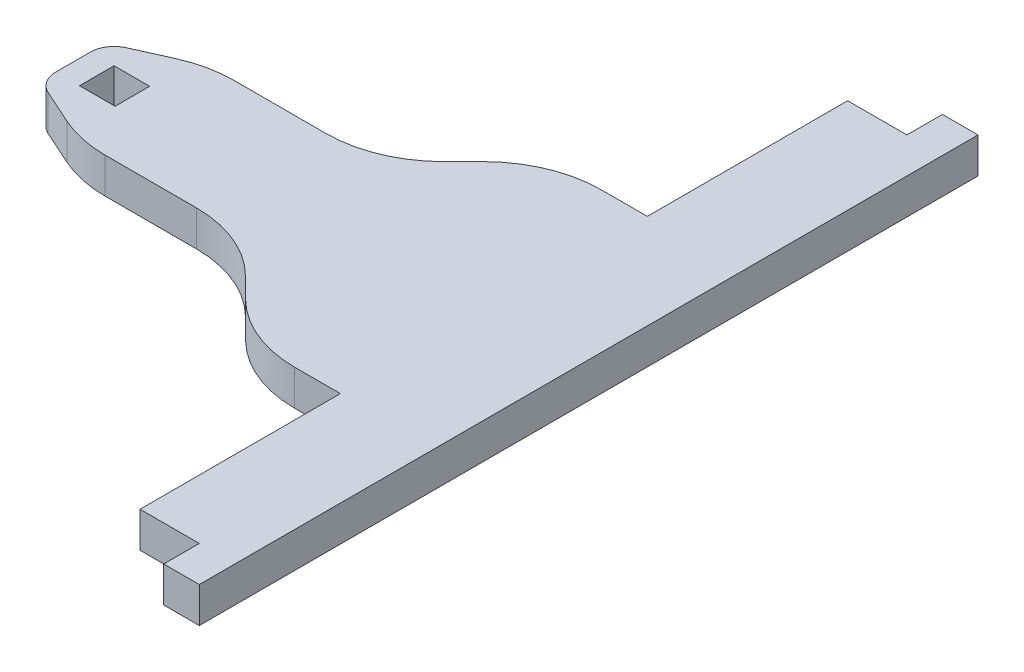
SolidWorks part; units mm, degrees
ref_plane "Front Plane" through (0, 0, 0) normal (0, 0, 1) x (1, 0, 0)
ref_plane "Top Plane" through (0, 0, 0) normal (0, 1, 0) x (1, 0, 0)
ref_plane "Right Plane" through (0, 0, 0) normal (1, 0, 0) x (0, 0, -1)
sketch "Sketch1" plane through (0, 0, 0) normal (0, 1, 0) x (1, 0, 0)
  line L1 (-8, -45.8) -> (-11.8579, -45.8)
  line L3 (-8, -19.9) -> (-11.8579, -19.9)
  line L14 (-43.5, -32.85) -> (0, -32.85) construction
  line L15 (-18.9289, -42.8711) -> (-20.5711, -41.2289)
  line L16 (-27.6421, -38.3) -> (-35.3537, -38.3)
  line L17 (-39.4573, -37.4192) -> (-42.3207, -36.1307)
  line L18 (-43.5, -34.3068) -> (-43.5, -31.3932)
  line L19 (-18.9289, -22.8289) -> (-20.5711, -24.4711)
  line L20 (-27.6421, -27.4) -> (-35.3537, -27.4)
  line L21 (-39.4573, -28.2808) -> (-42.3207, -29.5693)
  line L23 (0, -65.7) -> (-3, -65.7)
  line L24 (-3, -65.7) -> (-3, -62.7)
  line L25 (-3, -62.7) -> (-8, -62.7)
  line L26 (-8, -62.7) -> (-8, -45.8)
  line L27 (-8, -3) -> (-8, -19.9)
  line L28 (-3, -3) -> (-8, -3)
  line L29 (-3, 0) -> (-3, -3)
  line L30 (0, 0) -> (-3, 0)
  line L33 (0, 0) -> (0, -65.7)
  line L34 (-41.5, -34.3068) -> (-41.5, -31.3932)
  line L35 (-41.5, -31.3932) -> (-38.5, -31.3932)
  line L36 (-38.5, -31.3932) -> (-38.5, -34.3068)
  line L37 (-38.5, -34.3068) -> (-41.5, -34.3068)
  arc A0 (-18.9289, -42.8711) -> (-11.8579, -45.8) centre (-11.8579, -35.8) ccw
  arc A1 (-18.9289, -22.8289) -> (-11.8579, -19.9) centre (-11.8579, -29.9) cw
  arc A2 (-20.5711, -24.4711) -> (-27.6421, -27.4) centre (-27.6421, -17.4) cw
  arc A3 (-20.5711, -41.2289) -> (-27.6421, -38.3) centre (-27.6421, -48.3) ccw
  arc A4 (-35.3537, -38.3) -> (-39.4573, -37.4192) centre (-35.3537, -28.3) cw
  arc A5 (-35.3537, -27.4) -> (-39.4573, -28.2808) centre (-35.3537, -37.4) ccw
  arc A6 (-43.5, -34.3068) -> (-42.3207, -36.1307) centre (-41.5, -34.3068) ccw
  arc A7 (-43.5, -31.3932) -> (-42.3207, -29.5693) centre (-41.5, -31.3932) cw
  point P6 (-16, -45.8)
  point P19 (-43.5, -32.85)
  point P24 (-16, -45.8)
  point P28 (-16, -19.9)
  point P31 (-23.5, -27.4)
  point P34 (-23.5, -38.3)
  point P37 (-37.5, -38.3)
  point P40 (-37.5, -27.4)
  point P43 (-43.5, -35.6)
  point P46 (-43.5, -30.1)
  point P48 (0, 0)
  dimension "D11" = 10
  dimension "D14" = 2
  dimension "D2" = 7.5
  dimension "D3" = 7.5
  dimension "D4" = 6
  dimension "D5" = 2.7
  dimension "D6" = 14
  dimension "D7" = 19.9
  dimension "D8" = 3
  dimension "D9" = 3
  dimension "D10" = 5.5
  dimension "D12" = 5
  dimension "D13" = 8
  dimension "D15" = 3
extrude "Boss-Extrude1" add sketch "Sketch1" along normal blind 3
